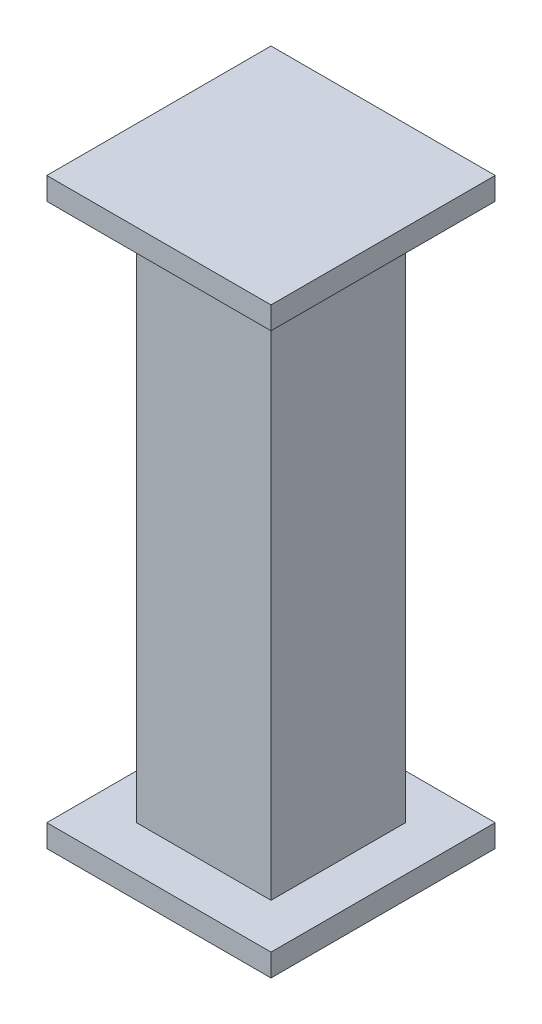
SolidWorks part; units mm, degrees
material "6061-T6 (SS)"
ref_plane "Alzado" through (0, 0, 0) normal (0, 0, 1) x (1, 0, 0)
ref_plane "Planta" through (0, 0, 0) normal (0, 1, 0) x (1, 0, 0)
ref_plane "Vista lateral" through (0, 0, 0) normal (1, 0, 0) x (0, 0, -1)
sketch "Sketch1" plane through (0, 0, 0) normal (0, 1, 0) x (1, 0, 0)
  line L1 (-6, 6) -> (6, 6)
  line L2 (-6, 6) -> (-6, -6)
  line L3 (-6, -6) -> (6, -6)
  line L4 (6, 6) -> (6, -6)
  line L5 (-6, 6) -> (6, -6) construction
  line L6 (-6, -6) -> (6, 6) construction
  line L7 (-4.5, 4.5) -> (4.5, 4.5)
  line L8 (-4.5, 4.5) -> (-4.5, -4.5)
  line L9 (-4.5, -4.5) -> (4.5, -4.5)
  line L10 (4.5, 4.5) -> (4.5, -4.5)
  line L11 (-4.5, 4.5) -> (4.5, -4.5) construction
  line L12 (-4.5, -4.5) -> (4.5, 4.5) construction
  point P0 (0, 0)
  point P6 (0, 0)
  dimension "D1" = 12
  dimension "D2" = 12
  dimension "D3" = 1.5
  dimension "D4" = 1.5
extrude "Boss-Extrude1" add sketch "Sketch1" along normal blind 48
sketch "Sketch3" plane through (0, 0, 0) normal (0, 1, 0) x (1, 0, 0)
  line L1 (-10, 10) -> (10, 10)
  line L2 (-10, 10) -> (-10, -10)
  line L3 (-10, -10) -> (10, -10)
  line L4 (10, 10) -> (10, -10)
  line L5 (-10, 10) -> (10, -10) construction
  line L6 (-10, -10) -> (10, 10) construction
  point P0 (0, 0)
  dimension "D1" = 20
  dimension "D2" = 20
extrude "Boss-Extrude2" add sketch "Sketch3" against normal blind 2
sketch "Sketch4" plane through (0, 48, 0) normal (0, 1, 0) x (1, 0, 0)
  line L1 (-10, 10) -> (10, 10)
  line L2 (-10, 10) -> (-10, -10)
  line L3 (-10, -10) -> (10, -10)
  line L4 (10, 10) -> (10, -10)
  line L5 (-10, 10) -> (10, -10) construction
  line L6 (-10, -10) -> (10, 10) construction
  point P0 (0, 0)
extrude "Boss-Extrude3" add sketch "Sketch4" along normal blind 2
